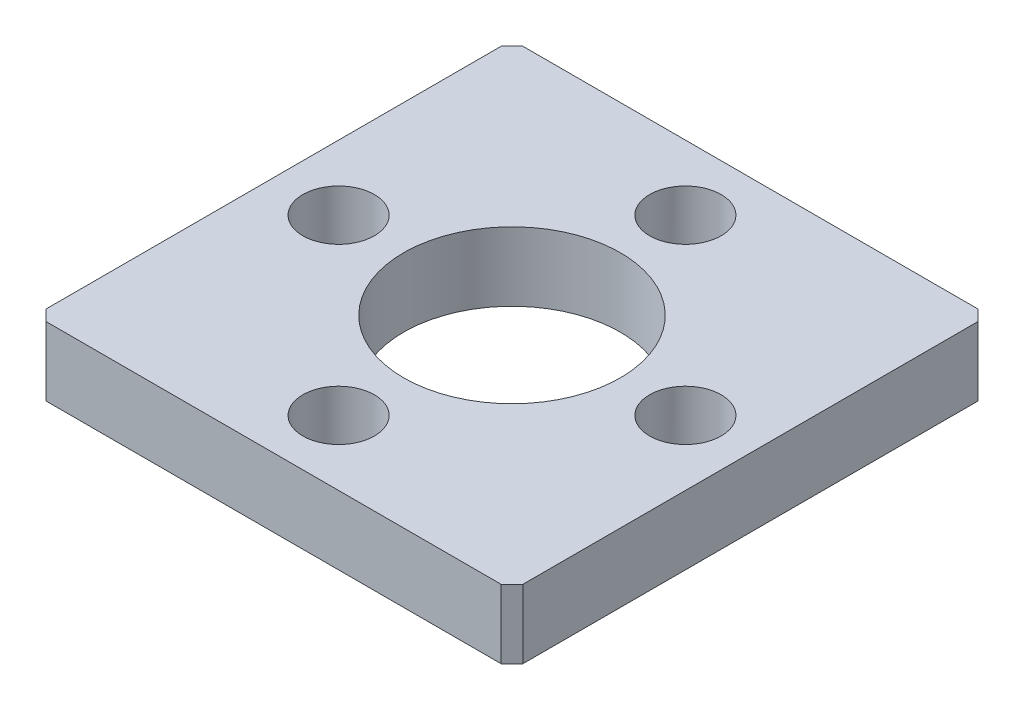
SolidWorks part; units mm, degrees
ref_plane "Front Plane" through (0, 0, 0) normal (0, 0, 1) x (1, 0, 0)
ref_plane "Top Plane" through (0, 0, 0) normal (0, 1, 0) x (1, 0, 0)
ref_plane "Right Plane" through (0, 0, 0) normal (1, 0, 0) x (0, 0, -1)
sketch "Sketch1" plane through (0, 0, 0) normal (0, 1, 0) x (1, 0, 0)
  line L1 (-11, -11) -> (11, -11)
  line L2 (-11, -11) -> (-11, 11)
  line L3 (-11, 11) -> (11, 11)
  line L4 (11, -11) -> (11, 11)
  line L5 (-11, -11) -> (11, 11) construction
  line L6 (-11, 11) -> (11, -11) construction
  point P0 (0, 0)
  dimension "D1" = 22
extrude "Boss-Extrude1" add sketch "Sketch1" along normal blind 3.175
sketch "Sketch2" plane through (0, 3.175, 0) normal (0, 1, 0) x (1, 0, 0)
  circle A0 centre (0, 0) radius 5
  dimension "D1" = 10
extrude "Cut-Extrude1" cut sketch "Sketch2" against normal through all
chamfer "Chamfer1" distance 0.5 angle 45 4 edges at (-11, 1.5875, -11) (11, 1.5875, -11) (11, 1.5875, 11) (-11, 1.5875, 11)
hole_wizard "Ø3.0mm Dowel Hole1" positions "Sketch3" profile "Sketch4" hole size "Ø3.0" standard "ANSI Metric"
sketch "Sketch3" plane through (0, 3.175, 0) normal (0, 1, 0) x (1, 0, 0)
  point P0 (8, 0)
  point P3 (0, -8)
  point P6 (-8, 0)
  point P9 (0, 8)
sketch "Sketch4" plane through (8, 3.175, 0) normal (1, 0, 0) x (0, 0, 1)
  line L0 (0, 0) -> (0, 15.9914)
  line L1 (0, 15.9914) -> (1.65, 15)
  line L2 (1.65, 15) -> (1.65, 0)
  line L5 (1.65, 0) -> (0, 0)
  line L10 (0, 15.9914) -> (-1.65, 15) construction
  line L11 (0, -6.35) -> (0, 107.95) construction
  dimension "Hole Dia." = 3.3
  dimension "Hole Depth" = 15
  dimension "Drill Angle" = 118
